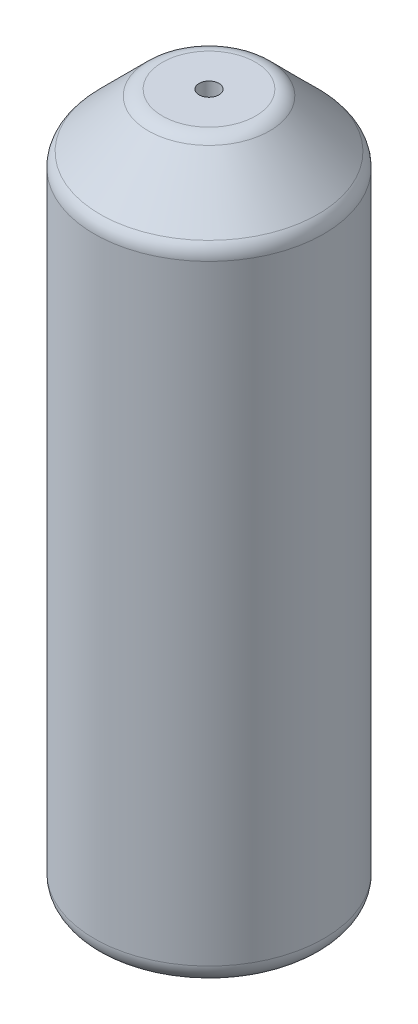
SolidWorks part; units mm, degrees
material "ABS"
ref_plane "Front Plane" through (0, 0, 0) normal (0, 0, 1) x (1, 0, 0)
ref_plane "Top Plane" through (0, 0, 0) normal (0, 1, 0) x (1, 0, 0)
ref_plane "Right Plane" through (0, 0, 0) normal (1, 0, 0) x (0, 0, -1)
sketch "Sketch1" plane through (0, 0, 0) normal (0, 0, 1) x (1, 0, 0)
  line L0 (0, -1000) -> (0, 49000) construction
  line L1 (5.75, 0) -> (5.75, 35)
  line L4 (0.7929, 32.7071) -> (1.7071, 31.7929)
  line L5 (4.125, 24) -> (4.125, 0)
  line L6 (4.125, 0) -> (5.75, 0)
  line L7 (0.5, 33.4142) -> (0.5, 35)
  line L8 (0.5, 35) -> (5.75, 35)
  line L9 (4.125, 29.375) -> (4.125, 25) construction
  line L10 (3.125, 25) -> (3, 25)
  line L11 (2, 26) -> (2, 31.0858)
  line L12 (2, 31.5) -> (4.125, 29.375) construction
  arc A0 (0.5, 33.4142) -> (0.7929, 32.7071) centre (1.5, 33.4142) ccw
  arc A1 (2, 31.0858) -> (1.7071, 31.7929) centre (1, 31.0858) ccw
  arc A2 (3, 25) -> (2, 26) centre (3, 26) cw
  arc A3 (4.125, 24) -> (3.125, 25) centre (3.125, 24) ccw
  point P14 (0.5, 33)
  point P21 (2, 25)
  dimension "D9" = 1
  dimension "D1" = 11.5
  dimension "D2" = 8.25
  dimension "D3" = 1
  dimension "D4" = 45
  dimension "D5" = 2
  dimension "D6" = 35
  dimension "D7" = 4
  dimension "D8" = 25
revolve "Revolve1" add sketch "Sketch1" angle 360 about L0
chamfer "Chamfer1" distance 3 angle 45 1 edges at (5.75, 35, 0)
fillet "Fillet1" radius 1 3 edges at (-2.75, 35, 0) (-5.75, 32, 0) (5.75, 0, 0)
chamfer "Chamfer2" distance 0.5 angle 45 1 edges at (4.125, 0, 0)
